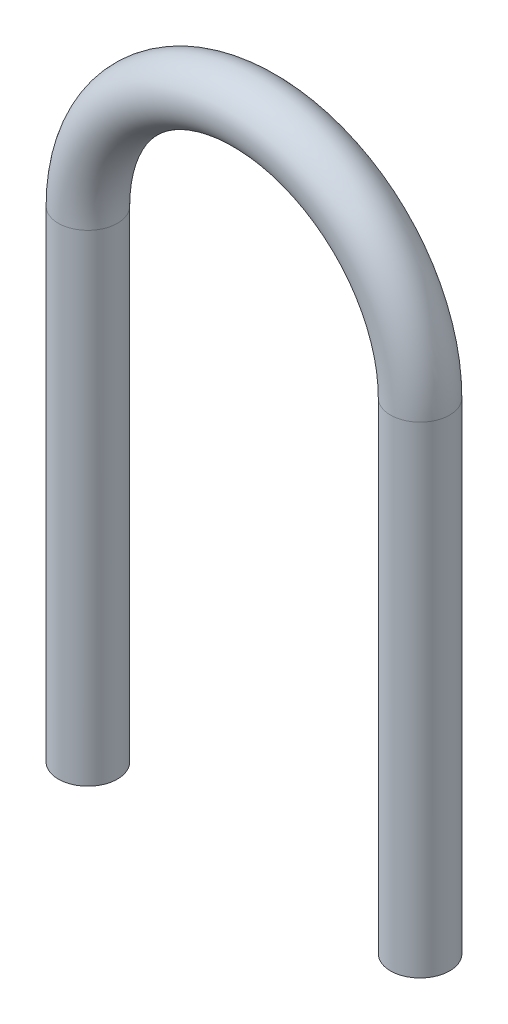
SolidWorks part; units mm, degrees
ref_plane "Alzado" through (0, 0, 0) normal (0, 0, 1) x (1, 0, 0)
ref_plane "Planta" through (0, 0, 0) normal (0, 1, 0) x (1, 0, 0)
ref_plane "Vista lateral" through (0, 0, 0) normal (1, 0, 0) x (0, 0, -1)
sketch "Croquis1" plane through (0, 0, 0) normal (0, 1, 0) x (1, 0, 0)
  line L0 (-13.3812, 0) -> (13.3812, 0) construction
  circle A0 centre (13.3812, 0) radius 2.3813
  point P4 (0, 0)
  dimension "D2" = 4.7625
  dimension "D1" = 26.7625
sketch "Croquis2" plane through (0, 0, 0) normal (0, 0, 1) x (1, 0, 0)
  line L0 (0, 38.7812) -> (0, 0) construction
  line L1 (-13.3812, 38.7812) -> (-13.3812, 0)
  line L2 (13.3812, 38.7812) -> (13.3812, 0)
  line L3 (-13.3812, 0) -> (13.3812, 0) construction
  line L4 (15.7625, 0) -> (11, 0) construction
  arc A0 (13.3812, 38.7812) -> (-13.3812, 38.7812) centre (0, 38.7812) ccw
  arc A1 (13.3812, 38.7812) -> (-13.3812, 38.7812) centre (0, 38.7812) cw construction
  point P8 (0, 25.4)
  dimension "D1" = 26.7625
  dimension "D2" = 25.4
sweep "Barrer1" add profiles "Croquis1" path "Croquis2"
equation "\"diametrodetuberia\"= 22mm"
equation "\"D1@Croquis1\"=\"diametrodetuberia\"+\"diamBirlo\""
equation "\"D1@Croquis2\"=\"diametrodetuberia\"+\"diamBirlo\""
equation "\"diamBirlo\"= 3pulgadas / 16"
equation "\"D2@Croquis1\"=\"diamBirlo\""
